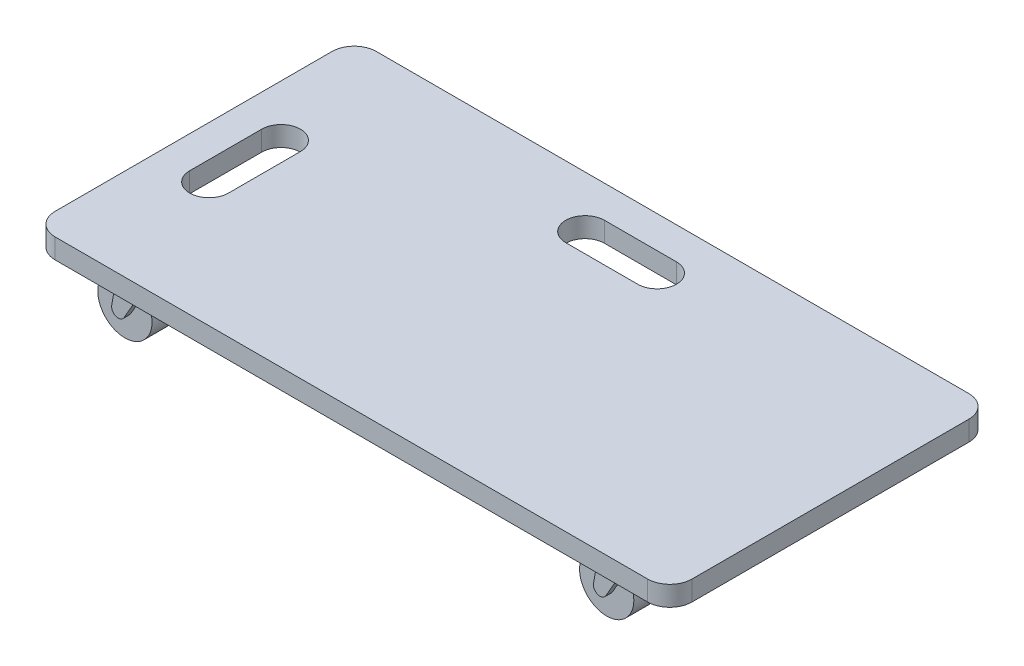
SolidWorks part; units mm, degrees
ref_plane "Plan de face" through (0, 0, 0) normal (0, 0, 1) x (1, 0, 0)
ref_plane "Plan de dessus" through (0, 0, 0) normal (0, 1, 0) x (1, 0, 0)
ref_plane "Plan de droite" through (0, 0, 0) normal (1, 0, 0) x (0, 0, -1)
sketch "Esquisse1" plane through (0, 0, 0) normal (0, 1, 0) x (1, 0, 0)
  line L0 (-241, 32.5) -> (-241, -32.5) construction
  line L1 (-287.5, -145) -> (287.5, -145)
  line L2 (-287.5, -145) -> (-287.5, 145)
  line L3 (-287.5, 145) -> (287.5, 145)
  line L4 (287.5, -145) -> (287.5, 145)
  line L5 (-287.5, -145) -> (287.5, 145) construction
  line L6 (-287.5, 145) -> (287.5, -145) construction
  line L7 (-223.5, 32.5) -> (-223.5, -32.5)
  line L8 (-258.5, 32.5) -> (-258.5, -32.5)
  line L9 (-32.5, 98.5) -> (32.5, 98.5) construction
  line L10 (-32.5, 116) -> (32.5, 116)
  line L11 (-32.5, 81) -> (32.5, 81)
  arc A0 (-223.5, 32.5) -> (-258.5, 32.5) centre (-241, 32.5) ccw
  arc A1 (-258.5, -32.5) -> (-223.5, -32.5) centre (-241, -32.5) ccw
  arc A2 (-32.5, 116) -> (-32.5, 81) centre (-32.5, 98.5) ccw
  arc A3 (32.5, 81) -> (32.5, 116) centre (32.5, 98.5) ccw
  point P0 (0, 0)
  point P8 (-241, 0)
  point P13 (0, 98.5)
  dimension "D1" = 290
  dimension "D2" = 575
  dimension "D3" = 35
  dimension "D4" = 65
  dimension "D5" = 29
  dimension "D6" = 29
extrude "Boss.-Extru.1" add sketch "Esquisse1" against normal blind 18
fillet "Congé1" radius 20 4 edges at (287.5, -9, -145) (-287.5, -9, -145) (-287.5, -9, 145) (287.5, -9, 145)
sketch "Esquisse2" plane through (0, -18, 0) normal (0, -1, 0) x (1, 0, 0)
  line L1 (-287.5, -125) -> (-287.5, 125) construction
  line L2 (-267.5, 145) -> (267.5, 145) construction
  circle A0 centre (-217.5, 100) radius 17.5
  dimension "D1" = 100
  dimension "D2" = 35
  dimension "D3" = 217.5
  dimension "D4" = 70
  dimension "D5" = 45
extrude "Boss.-Extru.2" add sketch "Esquisse2" along normal blind 18 separate body
sketch "Esquisse3" plane through (0, 0, 0) normal (0, 0, 1) x (1, 0, 0)
  line L0 (-245.4088, -56.9581) -> (-239.4211, -23)
  line L1 (-239.4211, -23) -> (-212.3645, -23)
  line L2 (-212.3645, -23) -> (-234.3038, -61)
  line L3 (-235, -36) -> (-200, -36) construction
  line L4 (-267.5, -18) -> (267.5, -18) construction
  arc A0 (-245.4088, -56.9581) -> (-234.3038, -61) centre (-239.5, -58) ccw
  point P1 (-217.5, -36)
  dimension "D1" = 22
  dimension "D3" = 6
  dimension "D2" = 40
  dimension "D4" = 100
  dimension "D5" = 5
  dimension "D6" = 60
extrude "Boss.-Extru.3" add sketch "Esquisse3" along normal mid plane 32 from offset 100
sketch "Esquisse4" plane through (0, 0, 0) normal (0, 0, 1) x (1, 0, 0)
  circle A0 centre (-239.5, -58) radius 24.5
  arc A1 (-245.4088, -56.9581) -> (-234.3038, -61) centre (-239.5, -58) ccw construction
  dimension "D1" = 49
extrude "Boss.-Extru.4" add sketch "Esquisse4" along normal mid plane 20 from offset 100 separate body
pattern_linear "Répétition linéaire1" count 2 spacing 435 along (1, 0, 0) count 2 spacing 200 along (0, 0, -1) of bodies 104 103
